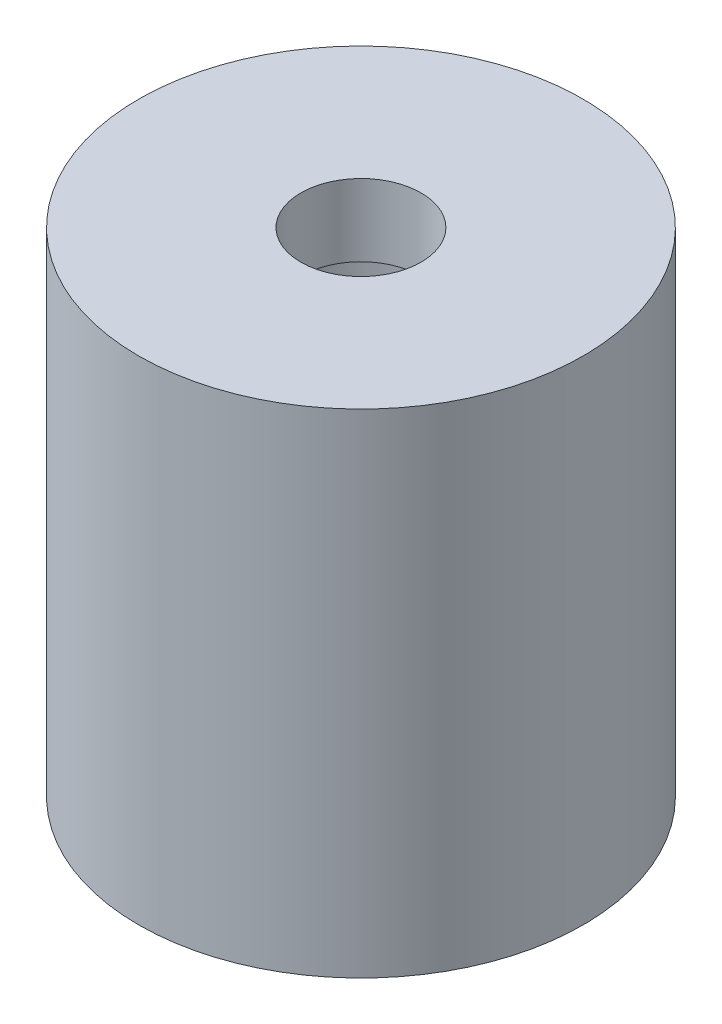
SolidWorks part; units mm, degrees
material "Настроенная пользователем пластмасса"
ref_plane "Спереди" through (0, 0, 0) normal (0, 0, 1) x (1, 0, 0)
ref_plane "Сверху" through (0, 0, 0) normal (0, 1, 0) x (1, 0, 0)
ref_plane "Справа" through (0, 0, 0) normal (1, 0, 0) x (0, 0, -1)
other "Configuration Table"
sketch "Эскиз1" plane through (0, 0, 0) normal (0, 1, 0) x (1, 0, 0)
  circle A0 centre (0, 0) radius 20
  circle A1 centre (0, 0) radius 37
  dimension "D1" = 40
  dimension "D2" = 74
extrude "Бобышка-Вытянуть1" add sketch "Эскиз1" along normal blind 70
sketch "Эскиз2" plane through (0, 70, 0) normal (0, 1, 0) x (1, 0, 0)
  circle A0 centre (0, 0) radius 37
  circle A1 centre (0, 0) radius 37 construction
  circle A2 centre (0, 0) radius 10
  dimension "D1" = 20
extrude "Бобышка-Вытянуть2" add sketch "Эскиз2" along normal blind 12
